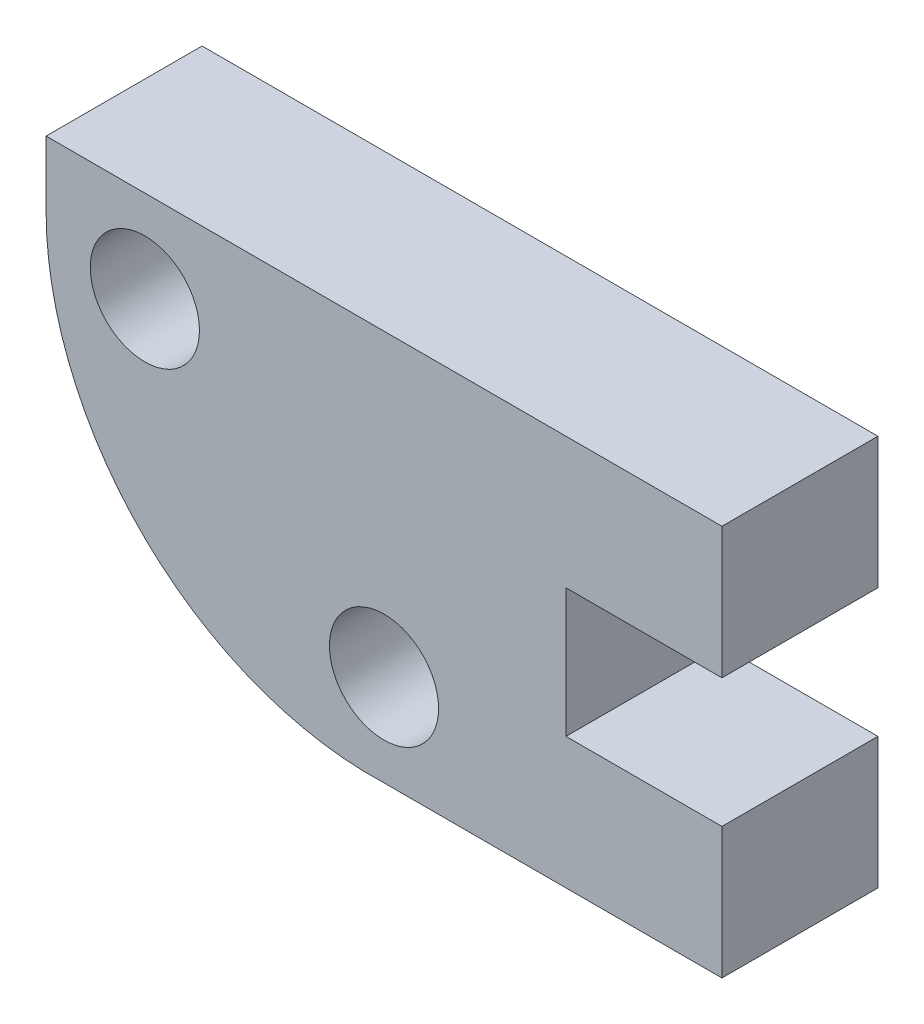
SolidWorks part; units mm, degrees
ref_plane "Plan de face" through (0, 0, 0) normal (0, 0, 1) x (1, 0, 0)
ref_plane "Plan de dessus" through (0, 0, 0) normal (0, 1, 0) x (1, 0, 0)
ref_plane "Plan de droite" through (0, 0, 0) normal (1, 0, 0) x (0, 0, -1)
sketch "Esquisse1" plane through (0, 0, 0) normal (0, 0, 1) x (1, 0, 0)
  line L0 (0, 0) -> (0, -5.05)
  line L1 (0, -5.05) -> (-6, -5.05)
  line L2 (-6, -5.05) -> (-6, -10)
  line L3 (-6, -10) -> (0, -10)
  line L4 (0, -10) -> (0, -15.05)
  line L5 (0, -15.05) -> (-13, -15.05)
  line L6 (-26, 0) -> (0, 0)
  line L7 (-22.2, -3.525) -> (-13, -3.525) construction
  line L8 (-13, -3.525) -> (-13, -11.525) construction
  line L9 (-22.2, -3.525) -> (-20.6153, -4.903) construction
  line L13 (-14.5847, -10.147) -> (-13, -11.525) construction
  line L14 (-26, 0) -> (-26, -2.5)
  circle A1 centre (-22.2, -3.525) radius 2.1
  circle A2 centre (-13, -11.525) radius 2.1
  arc A4 (-26, -2.5) -> (-13, -15.05) centre (-13.4422, -2.5) ccw
  point P17 (0, 0)
  point P18 (0, 0)
  point P19 (0, 0)
  point P20 (-39.695, 0)
  point P21 (0, 0)
  dimension "D5" = 4.2
  dimension "D6" = 4.2
  dimension "D10" = 26
  dimension "D1" = 6
  dimension "D2" = 5.05
  dimension "D3" = 4.95
  dimension "D4" = 5.05
  dimension "D7" = 9.2
  dimension "D8" = 8
  dimension "D9" = 3.525
  dimension "D11" = 7
  dimension "D12" = 2.5
extrude "Boss.-Extru.1" add sketch "Esquisse1" along normal blind 6
